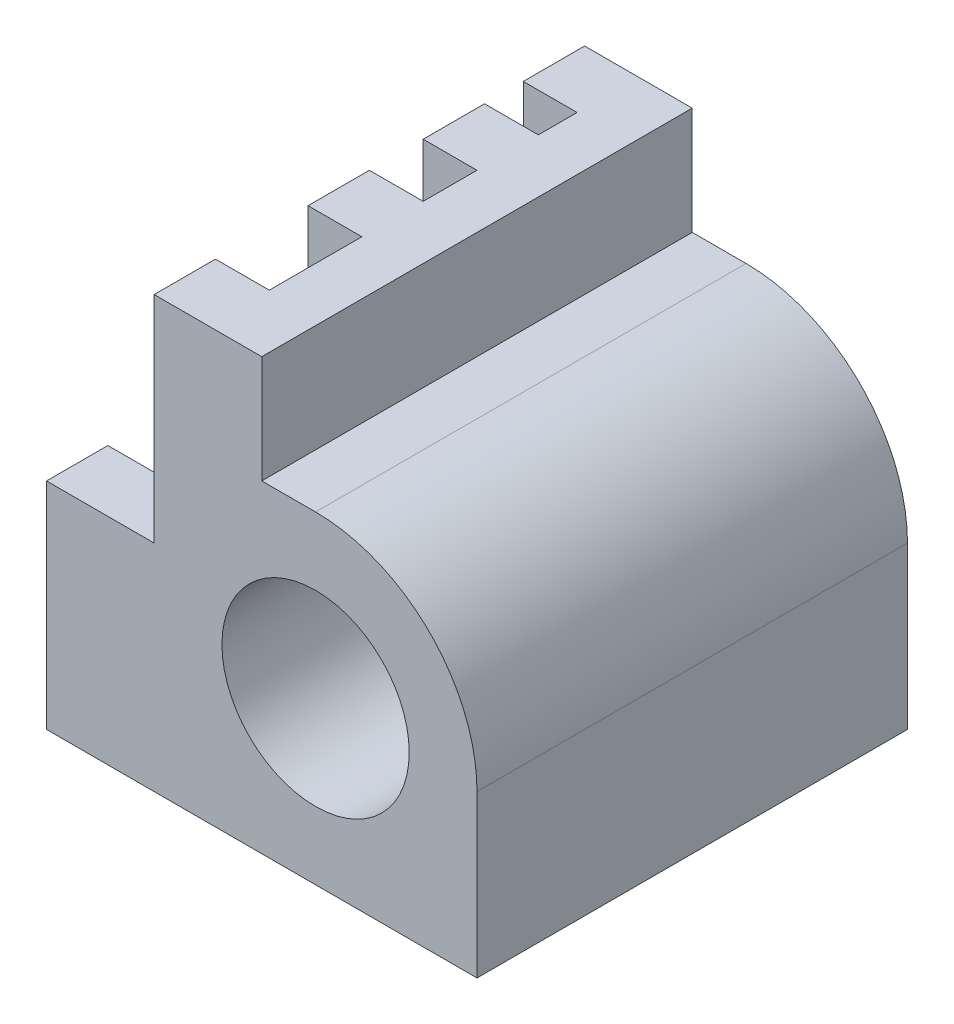
SolidWorks part; units mm, degrees
ref_plane "Front" through (0, 0, 0) normal (0, 0, 1) x (1, 0, 0)
ref_plane "Top" through (0, 0, 0) normal (0, 1, 0) x (1, 0, 0)
ref_plane "Right" through (0, 0, 0) normal (1, 0, 0) x (0, 0, -1)
sketch "Sketch1" plane through (0, 0, 0) normal (0, 0, 1) x (1, 0, 0)
  line L0 (0, 0) -> (20, 0)
  line L1 (20, 0) -> (20, 7.5)
  line L2 (12.5, 15) -> (10, 15)
  line L3 (10, 15) -> (10, 20)
  line L4 (10, 20) -> (5, 20)
  line L5 (5, 20) -> (5, 10)
  line L6 (5, 10) -> (0, 10)
  line L7 (0, 10) -> (0, 0)
  arc A0 (20, 7.5) -> (12.5, 15) centre (12.5, 7.5) ccw
  circle A1 centre (12.5, 7.5) radius 4.35
  point P12 (0, 0)
  dimension "D3" = 8.7
  dimension "D1" = 7.5
  dimension "D2" = 7.5
  dimension "D4" = 20
  dimension "D5" = 5
  dimension "D6" = 5
  dimension "D7" = 10
  dimension "D8" = 10
extrude "Boss-Extrude1" add sketch "Sketch1" along normal blind 20
sketch "Sketch2" plane through (0, 20, 0) normal (0, 1, 0) x (1, 0, 0)
  line L0 (0, -20) -> (0, 0) construction
  line L1 (7.5, -2.85) -> (0, -2.85)
  line L2 (7.5, -2.85) -> (7.5, -4.65)
  line L3 (7.5, -4.65) -> (0, -4.65)
  line L4 (0, -2.85) -> (0, -4.65)
  line L5 (7.5, -7.5) -> (0, -7.5)
  line L6 (7.5, -7.5) -> (7.5, -10)
  line L7 (7.5, -10) -> (0, -10)
  line L8 (0, -7.5) -> (0, -10)
  line L9 (7.5, -12.85) -> (0, -12.85)
  line L10 (7.5, -12.85) -> (7.5, -17.15)
  line L11 (7.5, -17.15) -> (0, -17.15)
  line L12 (0, -12.85) -> (0, -17.15)
  line L13 (0, -20) -> (0, -17.15) construction
  line L14 (0, -12.85) -> (0, -10) construction
  line L15 (0, -7.5) -> (0, -4.65) construction
  line L16 (0, -2.85) -> (0, 0) construction
  line L17 (5, -20) -> (5, 0) construction
  dimension "D1" = 1.8
  dimension "D2" = 2.5
  dimension "D3" = 4.3
  dimension "D4" = 2.5
extrude "Cut-Extrude1" cut sketch "Sketch2" against normal offset from surface (12.5 mm away) 2.5 up to face at (2.5, 10, 10) offset beyond the face yes
